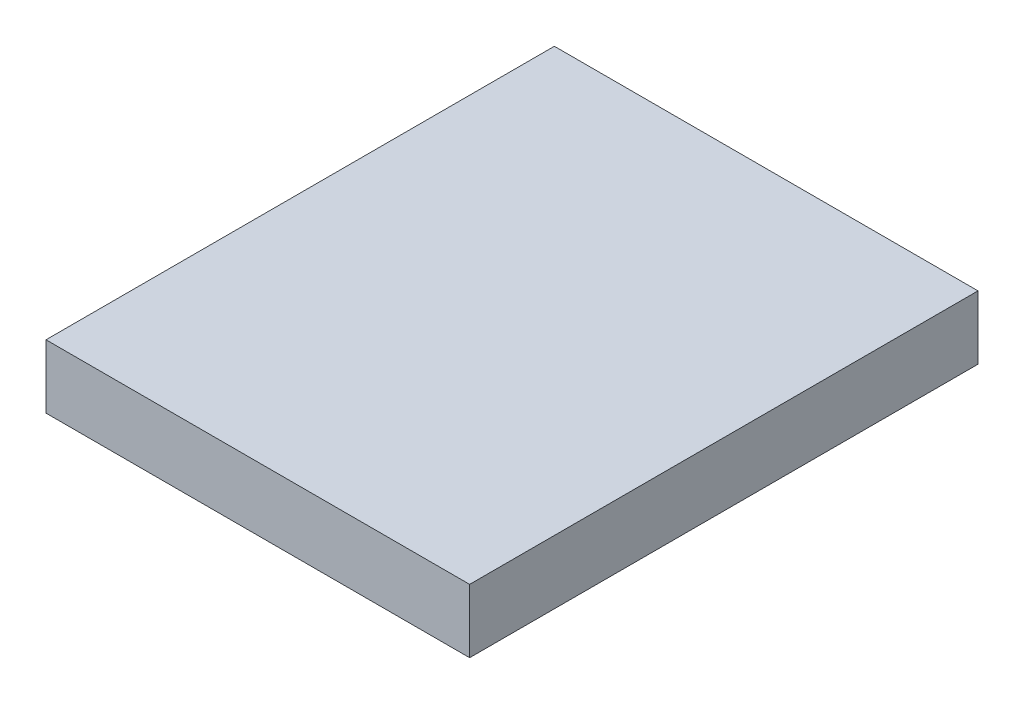
SolidWorks part; units mm, degrees
ref_plane "Front Plane" through (0, 0, 0) normal (0, 0, 1) x (1, 0, 0)
ref_plane "Top Plane" through (0, 0, 0) normal (0, 1, 0) x (1, 0, 0)
ref_plane "Right Plane" through (0, 0, 0) normal (1, 0, 0) x (0, 0, -1)
sketch "Sketch1" plane through (0, 0, 0) normal (0, 1, 0) x (1, 0, 0)
  line L1 (-2.5, -3) -> (2.5, -3)
  line L2 (-2.5, -3) -> (-2.5, 3)
  line L3 (-2.5, 3) -> (2.5, 3)
  line L4 (2.5, -3) -> (2.5, 3)
  line L5 (-2.5, -3) -> (2.5, 3) construction
  line L6 (-2.5, 3) -> (2.5, -3) construction
  point P0 (0, 0)
  dimension "D1" = 5
  dimension "D2" = 6
extrude "Boss-Extrude1" add sketch "Sketch1" along normal blind 0.75
